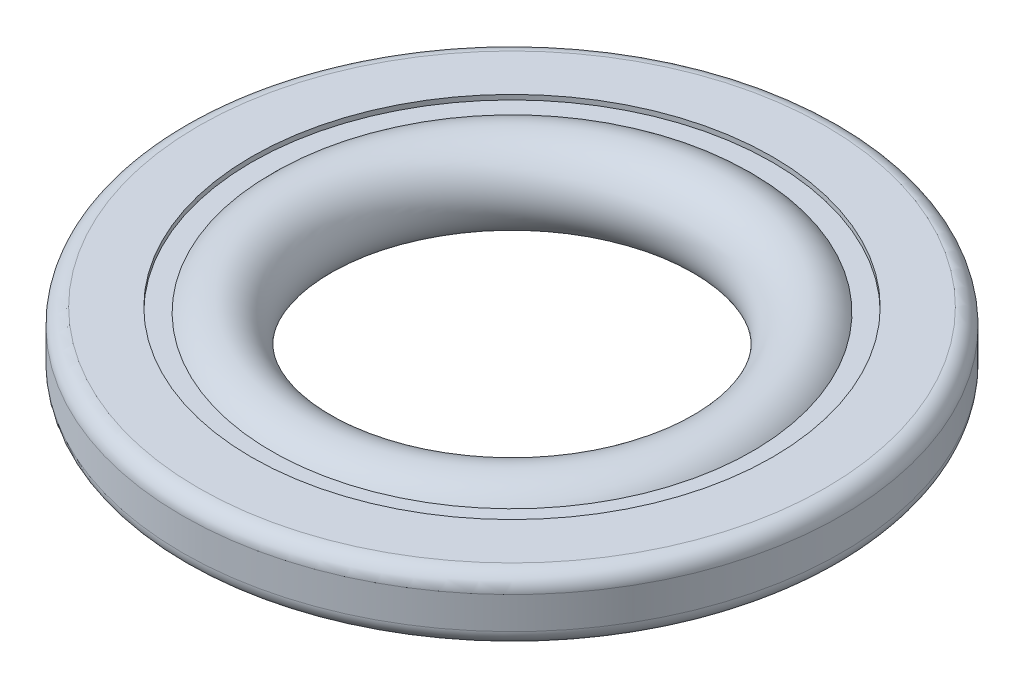
SolidWorks part; units mm, degrees
ref_plane "Front Plane" through (0, 0, 0) normal (0, 0, 1) x (1, 0, 0)
ref_plane "Top Plane" through (0, 0, 0) normal (0, 1, 0) x (1, 0, 0)
ref_plane "Right Plane" through (0, 0, 0) normal (1, 0, 0) x (0, 0, -1)
sketch "Sketch1" plane through (0, 0, 0) normal (0, 0, 1) x (1, 0, 0)
  line L0 (-4.6279, 0) -> (4.6279, 0) construction
  line L1 (0, 0) -> (0, 0.55) construction
  line L2 (-5.65, 0.55) -> (-5.65, -0.55) construction
  line L3 (-4.6279, 0.55) -> (-3.6, 0.55) construction
  line L4 (-4.6279, 0.55) -> (-4.6279, -0.55) construction
  line L5 (-4.6279, -0.55) -> (-3.6, -0.55) construction
  line L6 (-3.6, 0.55) -> (-3.6, -0.55) construction
  line L7 (-5.65, 0.4675) -> (-4.121, 0.4675) construction
  line L8 (-5.65, -0.4675) -> (-4.121, -0.4675) construction
  line L9 (2.9, 0) -> (-2.9, 0) construction
  line L10 (-4.6279, 0) -> (-4.3, 0)
  line L11 (5.65, 0) -> (-5.65, 0) construction
  circle A0 centre (-3.6, 0) radius 0.7 construction
  point P3 (-2.9, 0)
  point P18 (4.6279, -0.55)
  point P19 (-4.464, 0)
  point P21 (4.6279, 0.55)
  point P24 (0, 0)
  point P25 (-4.464, -0.4675)
  point P26 (-4.464, 0.4675)
  point P27 (5.65, 0.55)
  point P28 (5.65, -0.55)
  point P29 (5.65, -0.7)
  point P30 (5.65, 0.7)
  point P31 (-3.6, -0.7)
  point P32 (-5.65, 0.7)
  point P35 (0, 0)
  point P36 (-3.6, 0.7)
  point P37 (-5.65, -0.7)
  dimension "Max Thickness" = 1.4
  dimension "D2" = 8.6
  dimension "OD" = 11.3
  dimension "D4" = 0.935
  dimension "Thickness" = 1.1
  dimension "D1" = 9.2558
sketch "Sketch2" plane through (0, 0, 0) normal (0, 0, 1) x (1, 0, 0)
  line L1 (-5.65, 0.55) -> (-4.464, 0.55)
  line L5 (-4.464, -0.55) -> (-4.464, -0.4675)
  line L6 (-5.65, 0.4675) -> (-4.121, 0.4675) construction
  line L7 (-4.464, 0.4675) -> (-4.6279, 0.4675)
  line L8 (0, 0) -> (0, 0.55) construction
  line L9 (0, 0) -> (0, 0.55) construction
  line L10 (-4.6279, 0.55) -> (-4.6279, -0.55) construction
  line L12 (-4.6279, 0.4675) -> (-4.6279, -0.4675)
  line L13 (-4.6279, -0.4675) -> (-4.464, -0.4675)
  line L15 (-5.65, -0.4675) -> (-4.121, -0.4675) construction
  line L16 (-4.464, 0.4675) -> (-4.464, 0.55)
  line L18 (-4.464, -0.55) -> (-5.65, -0.55)
  line L19 (-5.65, -0.55) -> (-5.65, 0.55)
revolve "Revolve1" add sketch "Sketch2" angle 360 about L9
sketch "Sketch4" plane through (0, 0, 0) normal (0, 0, 1) x (1, 0, 0)
  line L1 (-4.6279, 0.4675) -> (-4.6279, -0.4675)
  line L2 (-5.65, 0.4675) -> (-4.121, 0.4675) construction
  line L3 (-4.6279, -0.4675) -> (-4.121, -0.4675)
  line L4 (-4.6279, 0.4675) -> (-4.121, 0.4675)
  line L6 (0, 0) -> (0, 0.55) construction
  line L7 (0, 0) -> (0, 0.55) construction
  circle A0 centre (-3.6, 0) radius 0.7 construction
  arc A1 (-4.121, -0.4675) -> (-4.121, 0.4675) centre (-3.6, 0) ccw
revolve "Revolve2" add sketch "Sketch4" angle 360 about L7
fillet "Fillet1" radius 0.275 2 edges at (0, 0.55, -5.65) (0, -0.55, -5.65)
equation "\"D4@Sketch1\" = \"Thickness@Sketch1\" * .85"
equation "\"D1@Sketch1\"=(\"OD@Sketch1\"+\"D2@Sketch1\")/2.15"
equation "\"D1@Fillet1\"=\"Thickness@Sketch1\" * .25"
